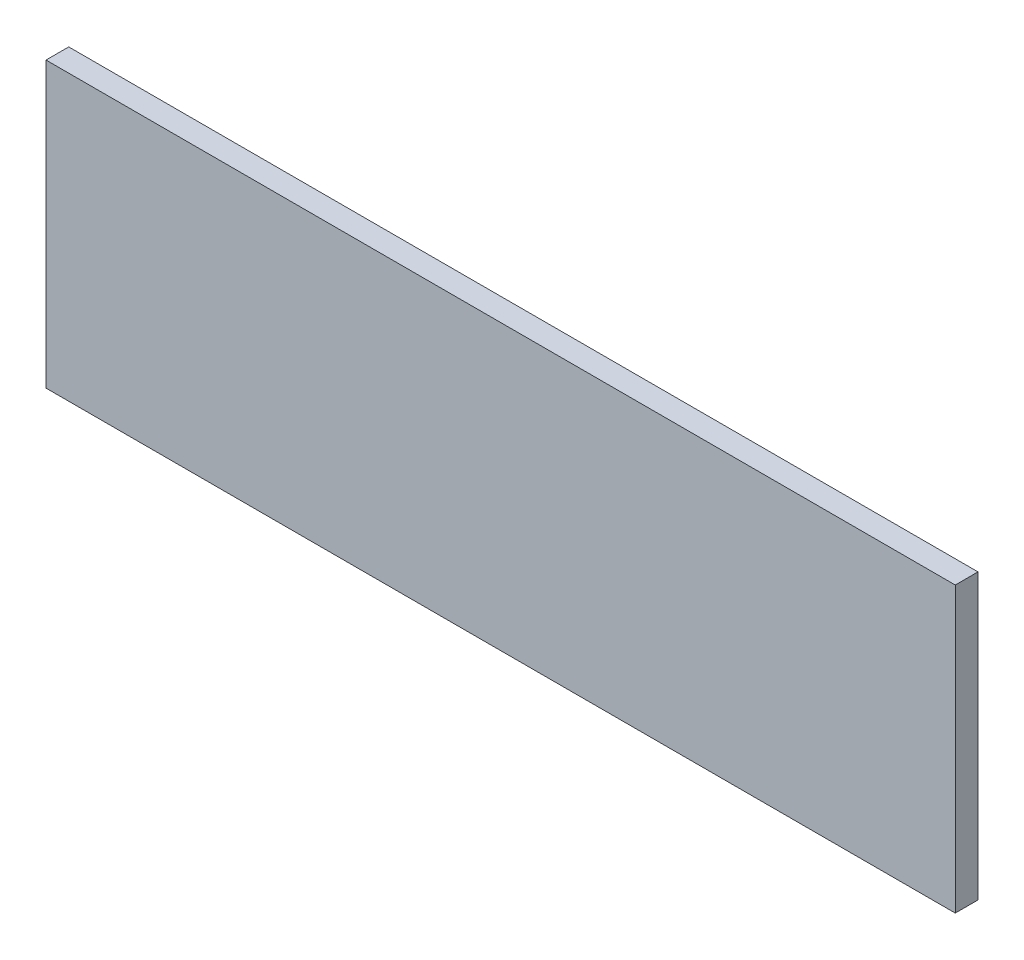
SolidWorks part; units mm, degrees
material "Plastique personnalisé"
ref_plane "Plan de face" through (0, 0, 0) normal (0, 0, 1) x (1, 0, 0)
ref_plane "Plan de dessus" through (0, 0, 0) normal (0, 1, 0) x (1, 0, 0)
ref_plane "Plan de droite" through (0, 0, 0) normal (1, 0, 0) x (0, 0, -1)
sketch "Esquisse1" plane through (0, 0, 0) normal (0, 0, 1) x (1, 0, 0)
  line L1 (-40, -12.5) -> (40, -12.5)
  line L2 (-40, -12.5) -> (-40, 12.5)
  line L3 (-40, 12.5) -> (40, 12.5)
  line L4 (40, -12.5) -> (40, 12.5)
  line L5 (-40, -12.5) -> (40, 12.5) construction
  line L6 (-40, 12.5) -> (40, -12.5) construction
  point P0 (0, 0)
  dimension "D1" = 80
  dimension "D2" = 25
extrude "Boss.-Extru.1" add sketch "Esquisse1" along normal blind 2
